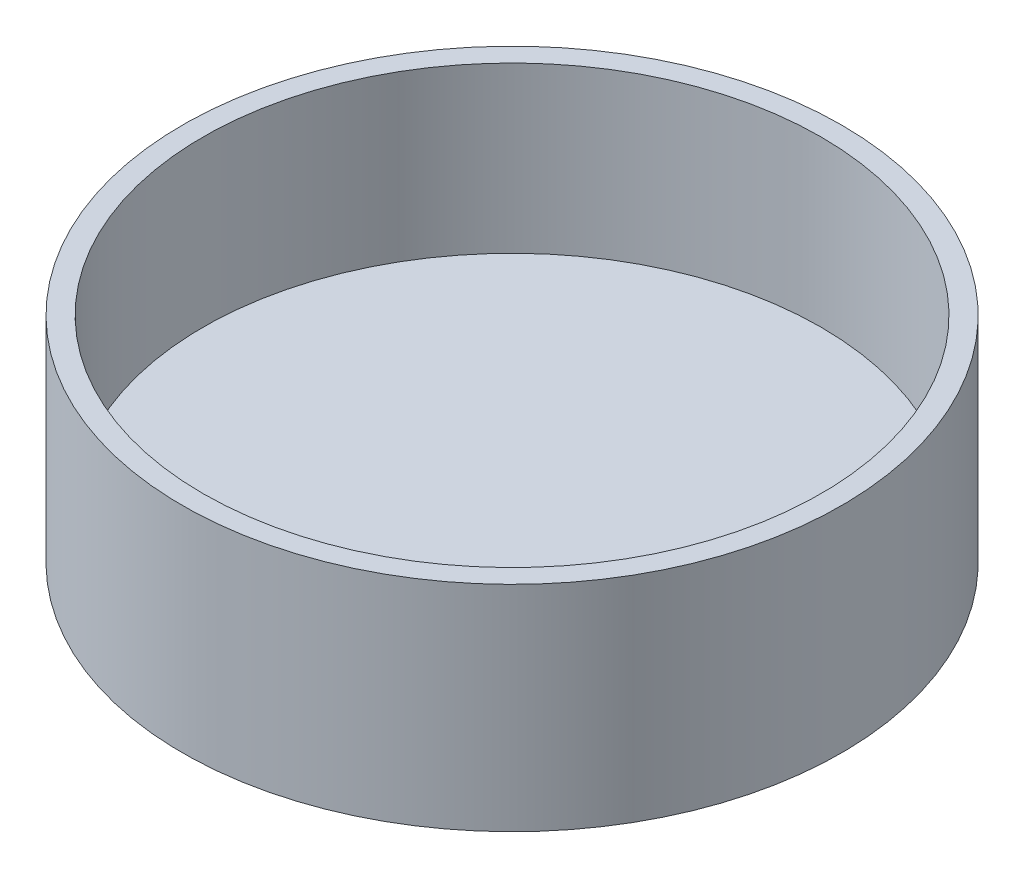
SolidWorks part; units mm, degrees
material "1060-H12"
ref_plane "Front Plane" through (0, 0, 0) normal (0, 0, 1) x (1, 0, 0)
ref_plane "Top Plane" through (0, 0, 0) normal (0, 1, 0) x (1, 0, 0)
ref_plane "Right Plane" through (0, 0, 0) normal (1, 0, 0) x (0, 0, -1)
sketch "Szkic2" plane through (0, 0, 0) normal (0, 1, 0) x (1, 0, 0)
  circle A0 centre (0, 0) radius 80
  dimension "D1" = 160
extrude "Dodanie-wyciągnięcie1" add sketch "Szkic2" along normal blind 52
sketch "Szkic3" plane through (0, 52, 0) normal (0, 1, 0) x (1, 0, 0)
  circle A0 centre (0, 0) radius 75
  dimension "D1" = 150
extrude "Wytnij-wyciągnięcie1" cut sketch "Szkic3" against normal blind 40 contours A0
